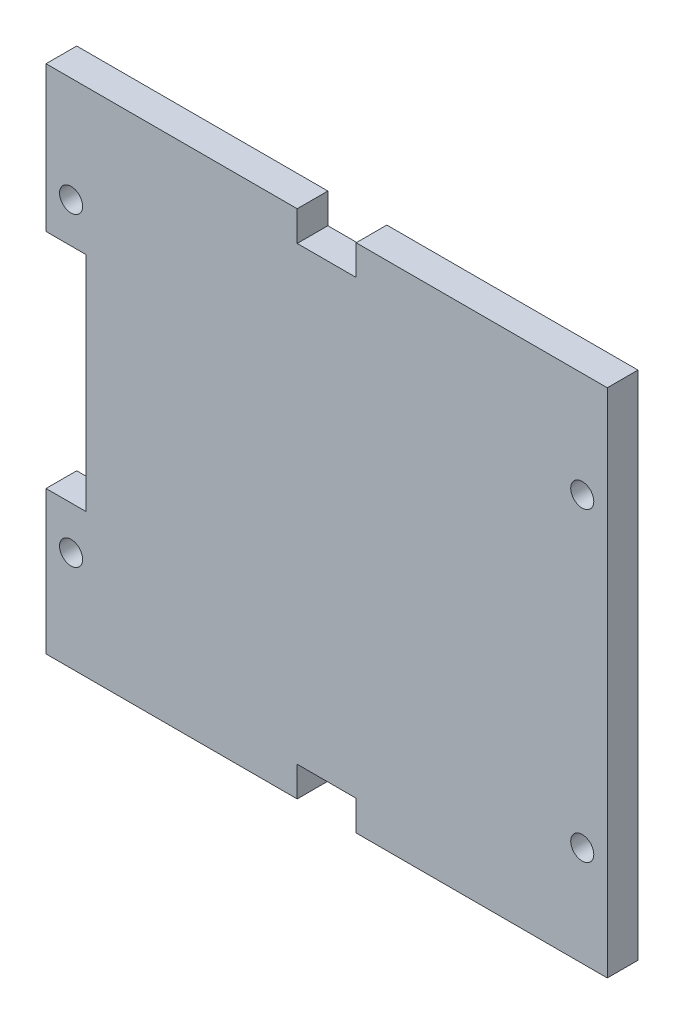
SolidWorks part; units mm, degrees
ref_plane "Front Plane" through (0, 0, 0) normal (0, 0, 1) x (1, 0, 0)
ref_plane "Top Plane" through (0, 0, 0) normal (0, 1, 0) x (1, 0, 0)
ref_plane "Right Plane" through (0, 0, 0) normal (1, 0, 0) x (0, 0, -1)
sketch "Sketch1" plane through (0, 0, 0) normal (0, 0, 1) x (1, 0, 0)
  line L1 (25.06, 0) -> (30.94, 0)
  line L2 (0, 0) -> (0, 45)
  line L3 (25.06, 45) -> (30.94, 45)
  line L4 (56, 0) -> (56, 45)
  line L6 (56, 45) -> (56, 48)
  line L7 (56, 48) -> (30.94, 48)
  line L8 (30.94, 45) -> (30.94, 48)
  line L10 (0, 45) -> (0, 48)
  line L11 (0, 48) -> (25.06, 48)
  line L12 (25.06, 45) -> (25.06, 48)
  line L14 (0, 0) -> (0, -3)
  line L15 (0, -3) -> (25.06, -3)
  line L16 (25.06, 0) -> (25.06, -3)
  line L18 (56, 0) -> (56, -3)
  line L19 (56, -3) -> (30.94, -3)
  line L20 (30.94, 0) -> (30.94, -3)
  dimension "D1" = 45
  dimension "D2" = 56
  dimension "D3" = 25.06
  dimension "D4" = 25.06
  dimension "D5" = 3
  dimension "D6" = 3
  dimension "D7" = 25.06
  dimension "D8" = 3
  dimension "D9" = 25.06
  dimension "D10" = 3
  dimension "D11" = 5.88
  dimension "D12" = 45
  dimension "D13" = 3
  dimension "D14" = 3
extrude "Boss-Extrude1" add sketch "Sketch1" along normal blind 3.06 contours L1 L20 L19 L18 L4 L6 L7 L8 L3 L12 L11 L10 L2 L14 L15 L16
sketch "Sketch2" plane through (0, 0, 3.06) normal (0, 0, 1) x (1, 0, 0)
  line L0 (56, -3) -> (30.94, -3) construction
  line L1 (0.5, 40) -> (55.5, 40) construction
  line L2 (0.5, 40) -> (0.5, 5) construction
  line L3 (0.5, 5) -> (55.5, 5) construction
  line L4 (55.5, 40) -> (55.5, 5) construction
  line L5 (56, -3) -> (56, 48) construction
  line L6 (0, 48) -> (0, -3) construction
  line L7 (0, 33.5) -> (4, 33.5)
  line L8 (0, 33.5) -> (0, 11.2981)
  line L9 (0, 11.2981) -> (4, 11.2981)
  line L10 (4, 33.5) -> (4, 11.2981)
  circle A0 centre (2.5, 37.5) radius 1.15
  circle A1 centre (53.5, 37.5) radius 1.15
  circle A2 centre (53.5, 7) radius 1.15
  circle A3 centre (2.5, 7) radius 1.15
  dimension "D7" = 2.3
  dimension "D8" = 2.5
  dimension "D9" = 2
  dimension "D10" = 2.3
  dimension "D11" = 2
  dimension "D12" = 2.5
  dimension "D13" = 2.3
  dimension "D14" = 2
  dimension "D15" = 2
  dimension "D16" = 2.3
  dimension "D17" = 2
  dimension "D18" = 2
  dimension "D1" = 35
  dimension "D2" = 55
  dimension "D3" = 8
  dimension "D4" = 0.5
  dimension "D5" = 6.5
  dimension "D6" = 4
extrude "Cut-Extrude1" cut sketch "Sketch2" against normal through all
